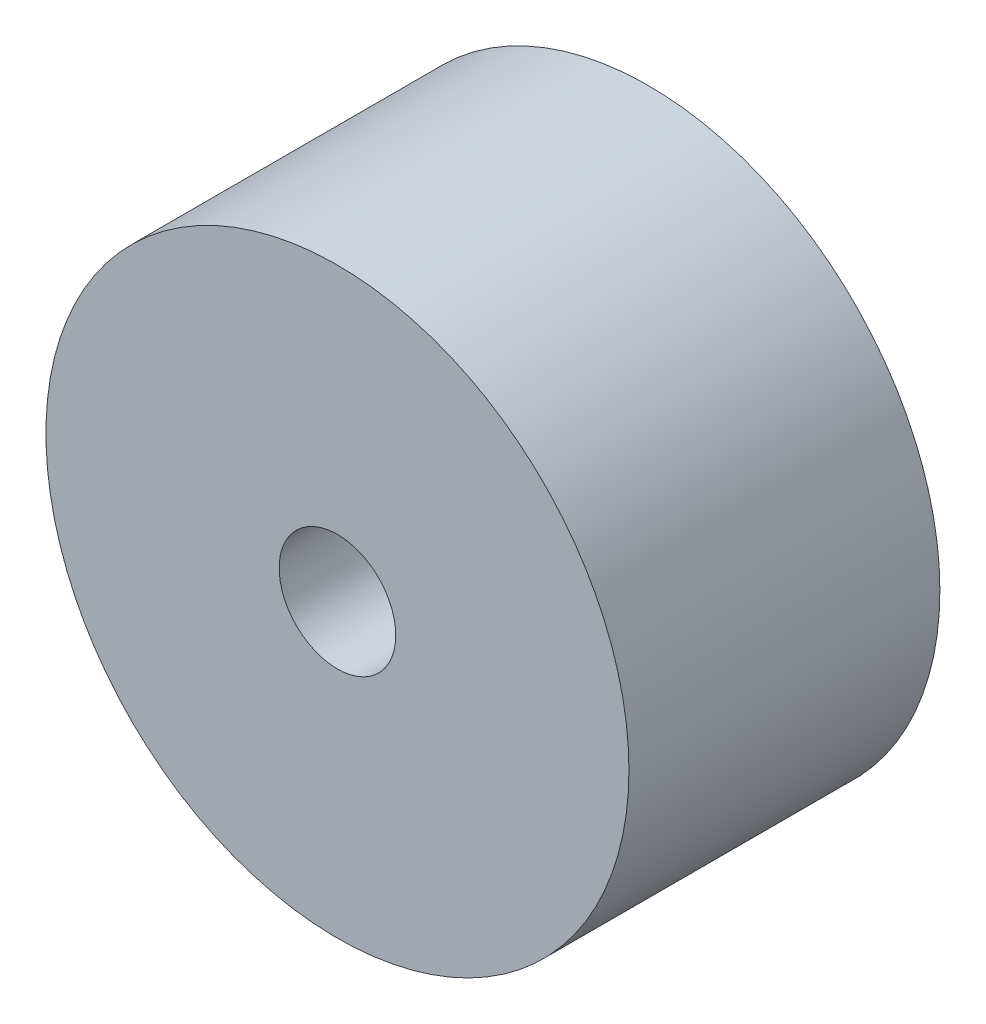
SolidWorks part; units mm, degrees
ref_plane "Front Plane" through (0, 0, 0) normal (0, 0, 1) x (1, 0, 0)
ref_plane "Top Plane" through (0, 0, 0) normal (0, 1, 0) x (1, 0, 0)
ref_plane "Right Plane" through (0, 0, 0) normal (1, 0, 0) x (0, 0, -1)
sketch "Sketch1" plane through (0, 0, 0) normal (0, 0, 1) x (1, 0, 0)
  circle A0 centre (-38.0825, 17.9321) radius 7.5
  circle A1 centre (-38.0825, 17.9321) radius 1.5
extrude "Boss-Extrude2" add sketch "Sketch1" along normal blind 8
